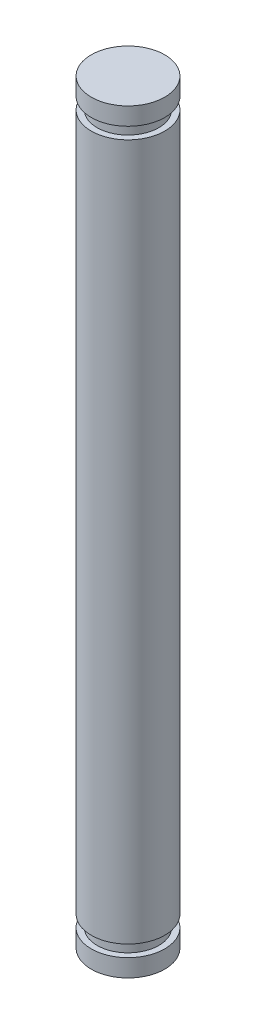
SolidWorks part; units mm, degrees
material "1060 Alloy"
ref_plane "Front Plane" through (0, 0, 0) normal (0, 0, 1) x (1, 0, 0)
ref_plane "Top Plane" through (0, 0, 0) normal (0, 1, 0) x (1, 0, 0)
ref_plane "Right Plane" through (0, 0, 0) normal (1, 0, 0) x (0, 0, -1)
sketch "Sketch1" plane through (0, 0, 0) normal (0, 1, 0) x (1, 0, 0)
  circle A0 centre (0, 0) radius 3.175
  dimension "D1" = 6.35
extrude "Boss-Extrude1" add sketch "Sketch1" along normal blind 60.198
sketch "Sketch2" plane through (0, 60.198, 0) normal (0, 1, 0) x (1, 0, 0)
  circle A0 centre (0, 0) radius 2.667
  dimension "D1" = 5.334
extrude "Boss-Extrude2" add sketch "Sketch2" along normal blind 1.016
sketch "Sketch3" plane through (0, 61.214, 0) normal (0, 1, 0) x (1, 0, 0)
  circle A0 centre (0, 0) radius 3.175
extrude "Boss-Extrude3" add sketch "Sketch3" along normal blind 1.524
sketch "Sketch4" plane through (0, 0, 0) normal (0, -1, 0) x (1, 0, 0)
  circle A0 centre (0, 0) radius 2.667
  dimension "D1" = 5.334
extrude "Boss-Extrude4" add sketch "Sketch4" along normal blind 1.016
sketch "Sketch7" plane through (0, -1.016, 0) normal (0, -1, 0) x (-1, 0, 0)
  circle A0 centre (0, 0) radius 3.175
extrude "Boss-Extrude5" add sketch "Sketch7" along normal blind 1.524
